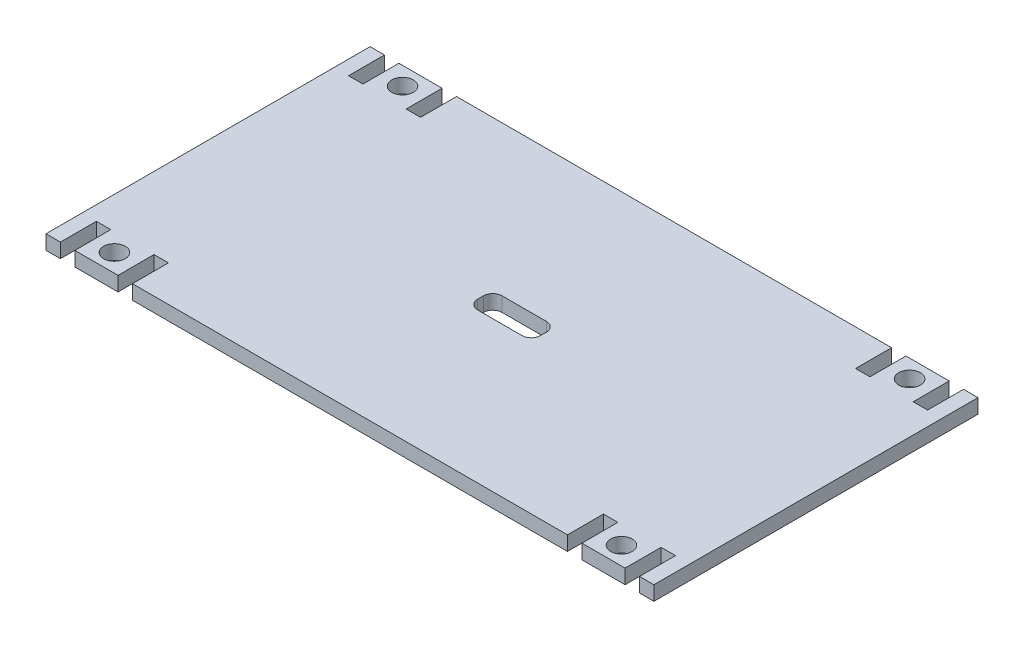
SolidWorks part; units mm, degrees
ref_plane "Front Plane" through (0, 0, 0) normal (0, 0, 1) x (1, 0, 0)
ref_plane "Top Plane" through (0, 0, 0) normal (0, 1, 0) x (1, 0, 0)
ref_plane "Right Plane" through (0, 0, 0) normal (1, 0, 0) x (0, 0, -1)
sketch "Sketch1" plane through (0, 0, 0) normal (0, 1, 0) x (1, 0, 0)
  line L0 (42.2, 45) -> (42.2, 0) construction
  line L1 (0, 0) -> (2, 0)
  line L2 (0, 0) -> (0, 45)
  line L3 (0, 45) -> (2, 45)
  line L4 (84.4, 0) -> (84.4, 45)
  line L5 (0, 22.5) -> (84.4, 22.5) construction
  line L6 (7, 45) -> (7, 42.5) construction
  line L7 (7, 42.5) -> (11, 42.5) construction
  line L9 (10, 40) -> (12, 40)
  line L10 (10, 40) -> (10, 45)
  line L12 (12, 40) -> (12, 45)
  line L13 (10, 40) -> (12, 45) construction
  line L14 (10, 45) -> (12, 40) construction
  line L15 (2, 40) -> (2, 45)
  line L16 (4, 40) -> (2, 40)
  line L17 (4, 40) -> (4, 45)
  line L19 (72.4, 40) -> (72.4, 45)
  line L20 (74.4, 40) -> (72.4, 40)
  line L21 (74.4, 40) -> (74.4, 45)
  line L22 (80.4, 40) -> (80.4, 45)
  line L23 (80.4, 40) -> (82.4, 40)
  line L24 (82.4, 40) -> (82.4, 45)
  line L27 (12, 5) -> (12, 0)
  line L28 (10, 5) -> (12, 5)
  line L29 (10, 5) -> (10, 0)
  line L30 (4, 5) -> (4, 0)
  line L31 (4, 5) -> (2, 5)
  line L32 (2, 5) -> (2, 0)
  line L35 (82.4, 5) -> (82.4, 0)
  line L36 (80.4, 5) -> (82.4, 5)
  line L37 (80.4, 5) -> (80.4, 0)
  line L38 (74.4, 5) -> (74.4, 0)
  line L39 (74.4, 5) -> (72.4, 5)
  line L40 (72.4, 5) -> (72.4, 0)
  line L42 (4, 0) -> (10, 0)
  line L43 (12, 0) -> (72.4, 0)
  line L44 (4, 45) -> (10, 45)
  line L45 (12, 45) -> (72.4, 45)
  line L46 (82.4, 45) -> (84.4, 45)
  line L47 (74.4, 45) -> (80.4, 45)
  line L48 (82.4, 0) -> (84.4, 0)
  line L49 (74.4, 0) -> (80.4, 0)
  circle A0 centre (7, 42.5) radius 1.5
  circle A1 centre (77.4, 42.5) radius 1.5
  circle A2 centre (7, 2.5) radius 1.5
  circle A3 centre (77.4, 2.5) radius 1.5
  dimension "D3" = 3
  dimension "D1" = 84.4
  dimension "D2" = 45
  dimension "D4" = 2
  dimension "D5" = 5
  dimension "D7" = 2
  dimension "D8" = 6
extrude "Boss-Extrude1" add sketch "Sketch1" along normal blind 2
sketch "Sketch2" plane through (0, 2, 0) normal (0, 1, 0) x (1, 0, 0)
  line L0 (42.2, 0) -> (42.2, 22.5) construction
  line L2 (37.825, 20.8) -> (46.575, 20.8)
  line L3 (12, 0) -> (72.4, 0) construction
  line L4 (37.825, 20.8) -> (37.825, 24.2)
  line L5 (37.825, 24.2) -> (46.575, 24.2)
  line L10 (46.575, 20.8) -> (46.575, 24.2)
  line L11 (37.825, 20.8) -> (46.575, 24.2) construction
  line L14 (37.825, 24.2) -> (46.575, 20.8) construction
  dimension "D1" = 8.75
  dimension "D2" = 3.4
  dimension "D3" = 22.5
extrude "Cut-Extrude1" cut sketch "Sketch2" against normal blind 10
fillet "Fillet1" radius 1.3 4 edges at (46.575, 1, -20.8) (46.575, 1, -24.2) (37.825, 1, -24.2) (37.825, 1, -20.8)
